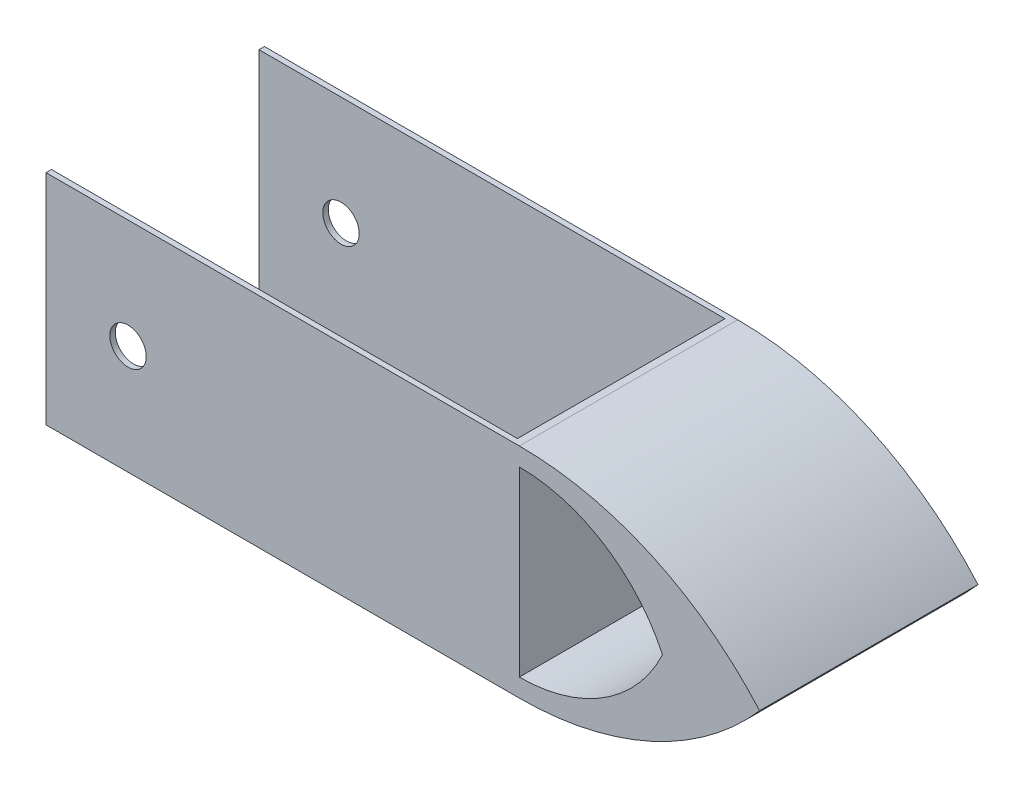
SolidWorks part; units mm, degrees
ref_plane "Plano frontal" through (0, 0, 0) normal (0, 0, 1) x (1, 0, 0)
ref_plane "Plano superior" through (0, 0, 0) normal (0, 1, 0) x (1, 0, 0)
ref_plane "Plano direito" through (0, 0, 0) normal (1, 0, 0) x (0, 0, -1)
sketch "Esboço1" plane through (0, 0, 0) normal (0, 0, 1) x (1, 0, 0)
  line L1 (65, 30) -> (-65, 30)
  line L3 (65, -30) -> (-65, -30)
  line L4 (-65, 30) -> (-65, -30)
  line L5 (65, 30) -> (-65, -30) construction
  line L6 (65, -30) -> (-65, 30) construction
  arc A0 (65, 30) -> (130.9931, 0) centre (65, -57.5849) cw
  arc A1 (65, -30) -> (130.9931, 0) centre (65, 57.5849) ccw
  point P0 (0, 0)
  dimension "D1" = 130
extrude "Ressalto-extrusão1" add sketch "Esboço1" along normal blind 60
sketch "Esboço3" plane through (0, 0, 0) normal (0, 0, 1) x (1, 0, 0)
  line L0 (65, 25) -> (65, -25)
  arc A0 (65, 25) -> (104.3393, 0) centre (65, -18.4516) cw
  arc A1 (65, -25) -> (104.3393, 0) centre (65, 18.4516) ccw
  dimension "D1" = 5
  dimension "D2" = 5
extrude "Corte-extrusão1" cut sketch "Esboço3" against normal through all and the other way through all
sketch "Esboço5" plane through (0, 0, 0) normal (0, 1, 0) x (1, 0, 0)
  line L0 (65, 0) -> (-65, 0) construction
  line L1 (63, -1.5) -> (-63, -1.5)
  line L2 (63, -1.5) -> (63, -58.5)
  line L3 (63, -58.5) -> (-63, -58.5)
  line L4 (-63, -1.5) -> (-63, -58.5)
  line L5 (63, -1.5) -> (-63, -58.5) construction
  line L6 (63, -58.5) -> (-63, -1.5) construction
  line L7 (65, -60) -> (-65, -60) construction
  line L8 (-65, -60) -> (-65, 0) construction
  line L9 (65, -60) -> (65, 0) construction
  point P0 (0, -30)
  dimension "D1" = 1.5
  dimension "D2" = 1.5
  dimension "D3" = 2
  dimension "D4" = 2
extrude "Corte-extrusão2" cut sketch "Esboço5" against normal through all both and the other way through all
sketch "Esboço6" plane through (-63, 0, 0) normal (1, 0, 0) x (0, 0, -1)
  line L1 (-1.5, -30) -> (-58.5, -30)
  line L2 (-1.5, -30) -> (-1.5, 30)
  line L3 (-1.5, 30) -> (-58.5, 30)
  line L4 (-58.5, -30) -> (-58.5, 30)
extrude "Corte-extrusão3" cut sketch "Esboço6" against normal blind 57
sketch "Esboço7" plane through (0, 0, 0) normal (0, 0, 1) x (1, 0, 0)
  circle A0 centre (-42.467, 0) radius 5
  dimension "D1" = 10
extrude "Corte-extrusão4" cut sketch "Esboço7" against normal blind 57 and the other way through all
